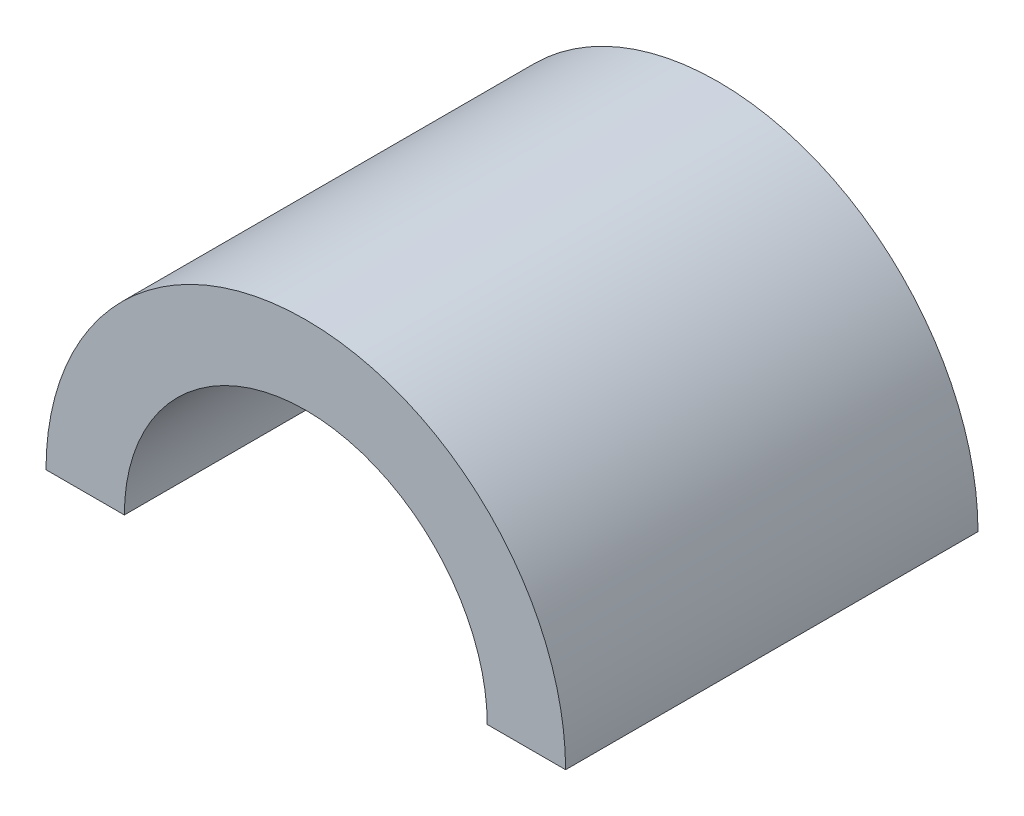
SolidWorks part; units mm, degrees
material "Natural Rubber"
ref_plane "Front Plane" through (0, 0, 0) normal (0, 0, 1) x (1, 0, 0)
ref_plane "Top Plane" through (0, 0, 0) normal (0, 1, 0) x (1, 0, 0)
ref_plane "Right Plane" through (0, 0, 0) normal (1, 0, 0) x (0, 0, -1)
sketch "Sketch1" plane through (0, 0, 0) normal (0, 0, 1) x (1, 0, 0)
  line L0 (-16.002, 0) -> (-11.176, 0)
  line L1 (11.176, 0) -> (16.002, 0)
  line L2 (-11.176, 0) -> (11.176, 0) construction
  arc A0 (11.176, 0) -> (-11.176, 0) centre (0, 0) ccw
  arc A1 (16.002, 0) -> (-16.002, 0) centre (0, 0) ccw
  dimension "D2" = 22.352
  dimension "D1" = 4.826
extrude "Boss-Extrude1" add sketch "Sketch1" along normal blind 25.4
equation "\"ThruHole\"=0.262"
equation "\"d_tube\"=0.88"
equation "\"t_rubber\"=0.19"
equation "\"w_rubber\"= .75"
equation "\"w_holder\"= \"d_tube\" + \"ThruHole\" * 7.5"
equation "\"D2@Sketch1\"=\"d_tube\""
equation "\"D1@Boss-Extrude1\"= \"L_holder\""
equation "\"D1@Sketch1\"=\"t_rubber\""
equation "\"L_holder\"= 1"
equation "\"fillet_1\"= 0.15"
equation "\"fillet_2\"= .11"
